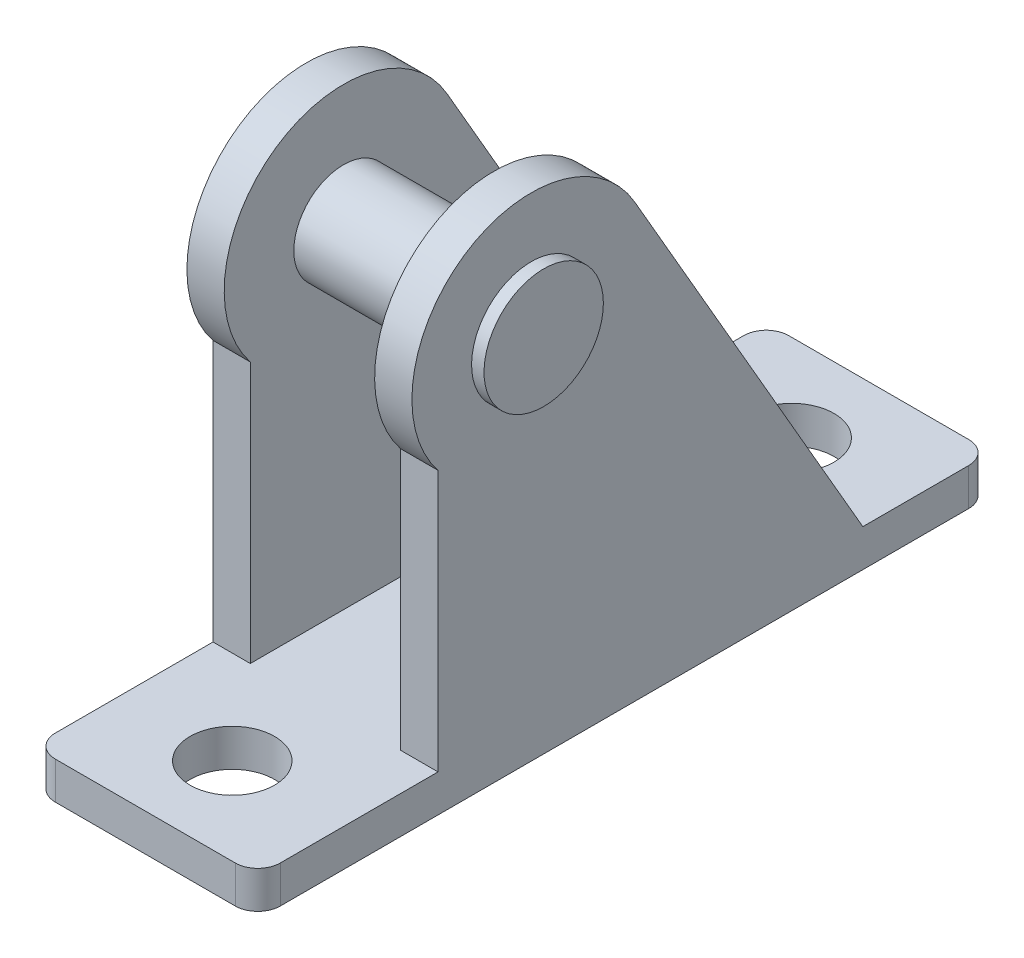
SolidWorks part; units mm, degrees
ref_plane "前视基准面" through (0, 0, 0) normal (0, 0, 1) x (1, 0, 0)
ref_plane "上视基准面" through (0, 0, 0) normal (0, 1, 0) x (1, 0, 0)
ref_plane "右视基准面" through (0, 0, 0) normal (1, 0, 0) x (0, 0, -1)
sketch "草图1" plane through (0, 0, 0) normal (1, 0, 0) x (0, 0, -1)
  line L0 (-22, 0) -> (0, 0) construction
  line L1 (0, 0) -> (0, 40) construction
  line L2 (0, 0) -> (37, 0) construction
  line L3 (-15, 0) -> (-15, 3) construction
  line L4 (0, 30) -> (-12, 30) construction
  line L5 (-7.5, 24.0075) -> (-7.5, 0)
  circle A1 centre (0, 30) radius 4
  circle A2 centre (0, 30) radius 9.6
  point P8 (-11.6, 0)
  point P12 (30, 0)
  dimension "D1" = 19.2
  dimension "BH" = 8
  dimension "D2" = 7.5
  dimension "BM" = 15
  dimension "BF" = 40
  dimension "BL" = 37
  dimension "AA" = 59
  dimension "BK" = 3
  dimension "BE" = 30
  dimension "BJ" = 6.8
  dimension "BG" = 12
  dimension "BB" = 30
sketch "草图2" plane through (0, 0, 0) normal (0, 0, 1) x (1, 0, 0)
  line L0 (-9.05, 0) -> (9.05, 0) construction
  line L1 (0, 0) -> (0, 40) construction
  line L3 (-16, 40) -> (16, 40) construction
  point P7 (-6.05, 40)
  point P8 (6.05, 40)
  dimension "BD" = 18.1
  dimension "BC" = 32
  dimension "BG1" = 12.1
sketch "草图3" plane through (0, 0, 0) normal (0, 0, 1) x (1, 0, 0)
  line L0 (-6.05, 3) -> (-6.05, 40)
  line L1 (9.05, 0) -> (9.05, 40)
  line L2 (-16, 40) -> (16, 40) construction
  line L3 (6.05, 3) -> (6.05, 40)
  line L4 (6.05, 40) -> (9.05, 40)
  line L5 (0, 0) -> (0, 3) construction
  line L6 (0, 0) -> (0, 30) construction
  line L7 (0, 26) -> (0, 34) construction
  line L8 (-9.05, 0) -> (9.05, 0)
  line L9 (-6.05, 3) -> (6.05, 3)
  line L10 (-9.05, 0) -> (-9.05, 40)
  line L12 (-9.05, 40) -> (-6.05, 40)
  point P22 (0, 3)
extrude "凸台-拉伸1" add sketch "草图3" along normal up to vertex (22 mm away) from vertex at -37 starting at point (0, 0, -37)
sketch "草图4" plane through (9.05, 0, 0) normal (1, 0, 0) x (0, 0, -1)
  line L0 (-7.5, 24.0075) -> (-7.5, 0) construction
  line L1 (-7.5, 24.0075) -> (-7.5, 3)
  line L2 (8.3138, 34.8) -> (26.6736, 3)
  line L3 (-7.5, 3) -> (-22, 3)
  line L4 (-22, 3) -> (-22, 40)
  line L5 (-22, 40) -> (37, 40)
  line L6 (26.6736, 3) -> (37, 3)
  line L7 (37, 3) -> (37, 40)
  circle A0 centre (0, 30) radius 9.6 construction
  arc A1 (8.3138, 34.8) -> (-7.5, 24.0075) centre (0, 30) ccw
  dimension "D1" = 30
extrude "切除-拉伸1" cut sketch "草图4" against normal through all
sketch "草图5" plane through (9.05, 0, 0) normal (1, 0, 0) x (0, 0, -1)
  circle A0 centre (0, 30) radius 4 construction
  circle A1 centre (0, 30) radius 4
extrude "凸台-拉伸2" add sketch "草图5" against normal up to surface (15.1 mm away) up to face at (-6.05, 18.3333, -3.5422)
sketch "草图6" plane through (9.05, 0, 0) normal (1, 0, 0) x (0, 0, -1)
  circle A0 centre (0, 30) radius 4.8
  dimension "D1" = 9.6
extrude "凸台-拉伸3" add sketch "草图6" along normal blind 1
mirror "镜向1" about plane through (0, 0, 0) normal (1, 0, 0) of "凸台-拉伸3"
fillet "圆角1" radius 1.81 4 edges at (-9.05, 1.5, -37) (9.05, 1.5, -37) (-9.05, 1.5, 22) (9.05, 1.5, 22)
sketch "草图7" plane through (0, 3, 0) normal (0, 1, 0) x (1, 0, 0)
  line L0 (0, -22) -> (0, 0) construction
  circle A0 centre (0, -15) radius 3.4
  circle A1 centre (0, 30) radius 3.4
extrude "切除-拉伸2" cut sketch "草图7" against normal through all
equation "\"D1@草图1\" = \"BG@草图1\"*2*0.8"
equation "\"D2@草图1\" = \"BM@草图1\"*0.5"
equation "\"D1@草图6\" = \"BH@草图1\"*1.2"
equation "\"D1@圆角1\" = \"BD@草图2\"*0.1"
